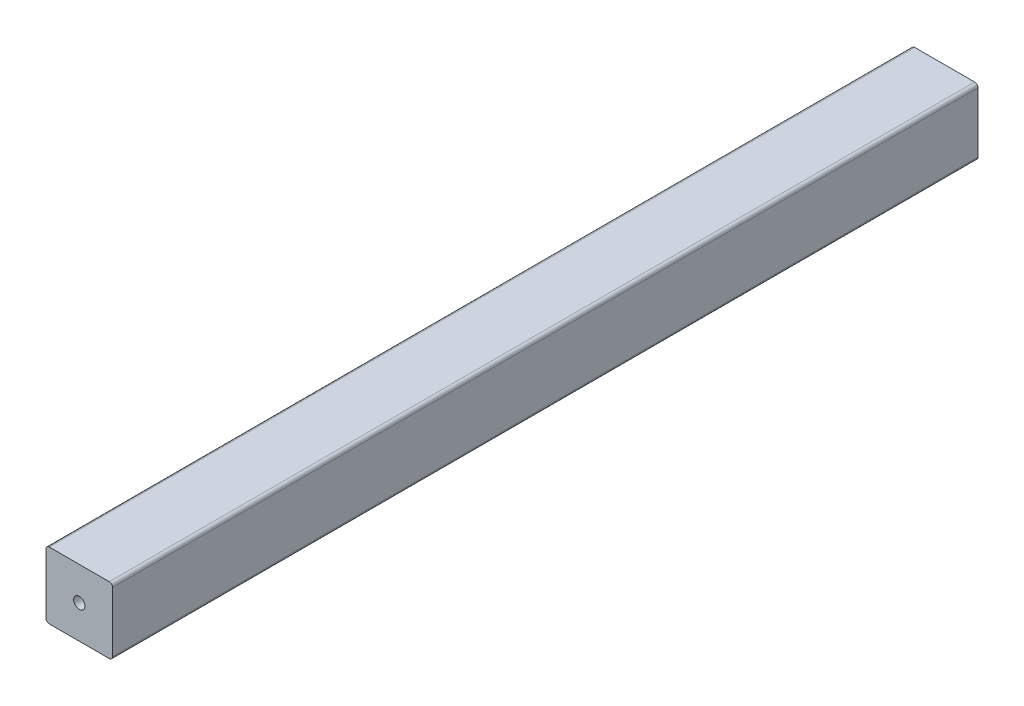
SolidWorks part; units mm, degrees
ref_plane "Front Plane" through (0, 0, 0) normal (0, 0, 1) x (1, 0, 0)
ref_plane "Top Plane" through (0, 0, 0) normal (0, 1, 0) x (1, 0, 0)
ref_plane "Right Plane" through (0, 0, 0) normal (1, 0, 0) x (0, 0, -1)
sketch "Sketch1" plane through (0, 0, 0) normal (0, 0, 1) x (1, 0, 0)
  line L1 (-20, -20) -> (20, -20)
  line L2 (-20, -20) -> (-20, 20)
  line L3 (-20, 20) -> (20, 20)
  line L4 (20, -20) -> (20, 20)
  line L5 (-20, -20) -> (20, 20) construction
  line L6 (-20, 20) -> (20, -20) construction
  circle A0 centre (0, 0) radius 2.5
  point P0 (0, 0)
  dimension "D3" = 5
  dimension "D1" = 40
  dimension "D2" = 40
extrude "Boss-Extrude1" add sketch "Sketch1" along normal mid plane 520
fillet "Fillet1" radius 2 4 edges at (20, -20, 0) (-20, -20, 0) (-20, 20, 0) (20, 20, 0)
sketch "Sketch2" plane through (0, 20, 0) normal (0, 1, 0) x (1, 0, 0)
  line L0 (0, 958.3172) -> (0, -945.7078) construction
  line L2 (18, 260) -> (-18, 260) construction
  line L3 (18, -260) -> (-18, -260) construction
  point P3 (0, -340)
  point P4 (0, 340)
  dimension "D1" = 600
  dimension "D2" = 600
hole_wizard "Ø4.5 (4.5) Diameter Hole1" positions "Sketch3" profile "Sketch4" hole size "Ø4.5" standard "ISO"
sketch "Sketch3" plane through (0, 20, 0) normal (0, 1, 0) x (1, 0, 0)
  point P0 (0, -300)
  point P3 (0, 300)
sketch "Sketch4" plane through (0, 20, 300) normal (1, 0, 0) x (0, 0, 1)
  line L0 (0, 0) -> (0, 40)
  line L1 (0, 40) -> (2.25, 40)
  line L2 (2.25, 40) -> (2.25, 0)
  line L5 (2.25, 0) -> (0, 0)
  line L11 (0, -6.35) -> (0, 107.95) construction
  dimension "Thru Hole Dia." = 4.5
  dimension "Thru Hole Depth" = 40
sketch "Sketch5" plane through (0, -20, 0) normal (0, -1, 0) x (1, 0, 0)
  line L0 (0, 260) -> (0, -1000.0028) construction
  line L1 (-18, 260) -> (18, 260) construction
  point P5 (0, 500)
  point P6 (0, 0)
  point P7 (0, -500)
  dimension "D1" = 500
  dimension "D2" = 500
hole_wizard "CBORE for M8 Hex Head Bolt1" positions "Sketch6" profile "Sketch7" counterbore size "M8" standard "ANSI Metric"
sketch "Sketch6" plane through (0, -20, 0) normal (0, -1, 0) x (-1, 0, 0)
  point P0 (0, 500)
  point P3 (0, 0)
  point P6 (0, -500)
sketch "Sketch7" plane through (0, -20, -500) normal (1, 0, 0) x (0, 0, -1)
  line L0 (0, 0) -> (0, 40)
  line L1 (0, 40) -> (4.5, 40)
  line L3 (4.5, 40) -> (4.5, 12.3)
  line L4 (4.5, 12.3) -> (9.005, 12.3)
  line L5 (9.005, 12.3) -> (9.005, 0)
  line L7 (9.005, 0) -> (0, 0)
  line L11 (0, -6.35) -> (0, 107.95) construction
  dimension "Thru Hole Dia." = 9
  dimension "Thru Hole Depth" = 40
  dimension "C'Bore Dia." = 18.01
  dimension "C'Bore Depth" = 12.3
hole_wizard "M8 Tapped Hole1" positions "Sketch8" profile "Sketch9" tap size "M8" standard "ISO"
sketch "Sketch8" plane through (0, 0, 260) normal (0, 0, 1) x (1, 0, 0)
  point P0 (0, 0)
sketch "Sketch9" plane through (0, 0, 260) normal (1, 0, 0) x (0, -1, 0)
  line L0 (0, 0) -> (0, 29.7929)
  line L1 (0, 29.7929) -> (3.4, 27.75)
  line L2 (3.4, 27.75) -> (3.4, 0)
  line L5 (3.4, 0) -> (0, 0)
  line L10 (0, 29.7929) -> (-3.4, 27.75) construction
  line L11 (0, -6.35) -> (0, 107.95) construction
  dimension "Tap Drill Dia." = 6.8
  dimension "Tap Drill Depth" = 27.75
  dimension "Drill Angle" = 118
cosmetic thread "Hole Thread1" parameters "D1"=24, "D2"=8
mirror "Mirror1" about plane through (0, 0, 0) normal (0, 0, 1) of "M8 Tapped Hole1"
cosmetic thread "Hole Thread2" parameters "D1"=24, "D2"=8
